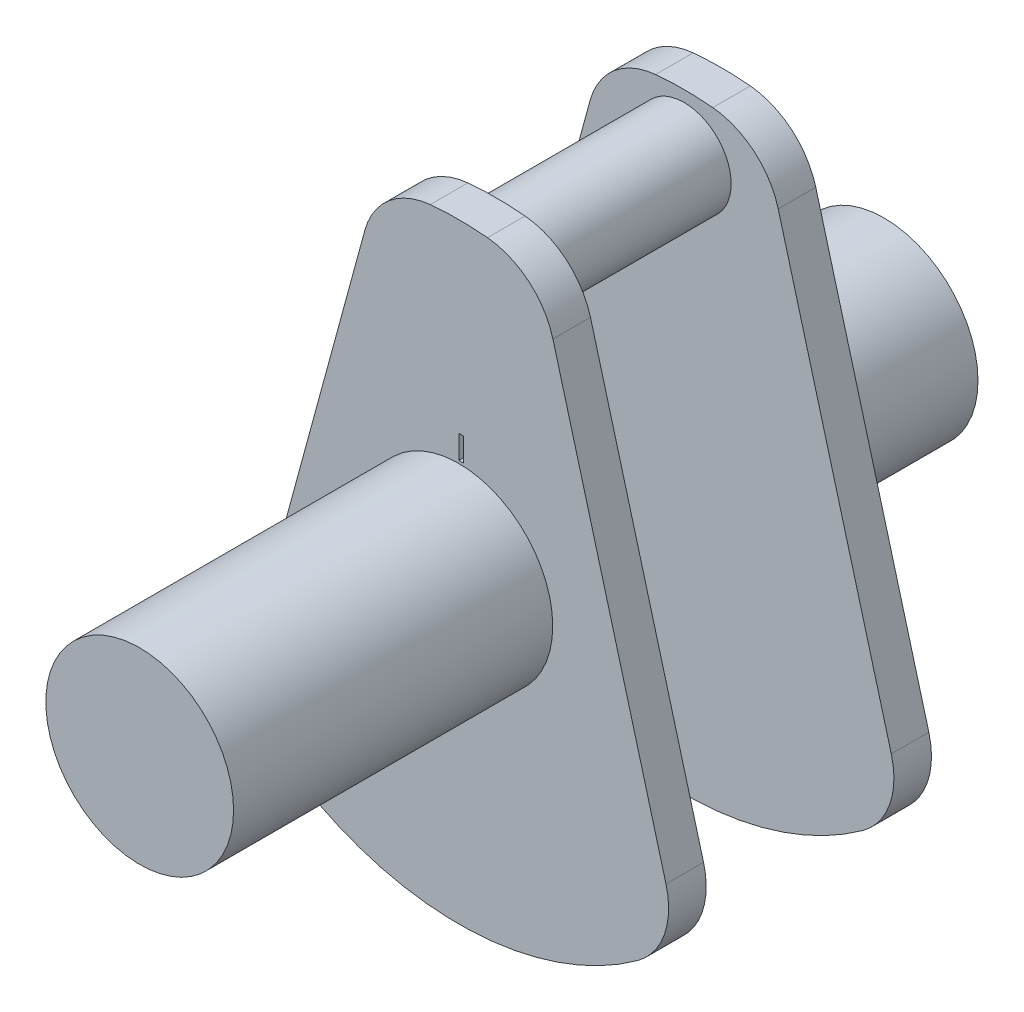
SolidWorks part; units mm, degrees
ref_plane "Front Plane" through (0, 0, 0) normal (0, 0, 1) x (1, 0, 0)
ref_plane "Top Plane" through (0, 0, 0) normal (0, 1, 0) x (1, 0, 0)
ref_plane "Right Plane" through (0, 0, 0) normal (1, 0, 0) x (0, 0, -1)
sketch "Sketch1" plane through (0, 0, 0) normal (0, 0, 1) x (1, 0, 0)
  line L0 (-2.0038, 5.2985) -> (-4.4127, -3.5522)
  line L1 (0, 6.5) -> (0, -6.5) construction
  line L2 (2.0038, 5.2985) -> (4.4127, -3.5522)
  arc A0 (-3.8056, -5.2695) -> (3.8056, -5.2695) centre (0, 0) ccw
  arc A1 (0.6102, 6.4713) -> (-0.6102, 6.4713) centre (0, 0) ccw
  arc A2 (2.0038, 5.2985) -> (0.6102, 6.4713) centre (0.46, 4.8784) ccw
  arc A3 (-2.0038, 5.2985) -> (-0.6102, 6.4713) centre (-0.46, 4.8784) cw
  arc A4 (-4.4127, -3.5522) -> (-3.8056, -5.2695) centre (-2.8688, -3.9724) ccw
  arc A5 (4.4127, -3.5522) -> (3.8056, -5.2695) centre (2.8688, -3.9724) cw
  point P10 (1.7415, 6.2624)
  point P13 (-1.7415, 6.2624)
  point P16 (-4.675, -4.516)
  point P19 (4.675, -4.516)
  dimension "D1" = 13
  dimension "D4" = 1.6
  dimension "D5" = 1.6
  dimension "D2" = 30.45
  dimension "D3" = 0.92
extrude "Boss-Extrude1" add sketch "Sketch1" along normal blind 0.8
sketch "Sketch3" plane through (0, 0, 0.8) normal (0, 0, 1) x (1, 0, 0)
  line L0 (0, 6.7111) -> (0, 5.26) construction
  circle A0 centre (0, 5.26) radius 1
  dimension "D1" = 2
  dimension "D2" = 5.26
extrude "Boss-Extrude2" add sketch "Sketch3" along normal blind 2
sketch "Sketch4" plane through (0, 0, 0) normal (0, 0, -1) x (-1, 0, 0)
  circle A0 centre (0, 0) radius 2
  dimension "D1" = 4
extrude "Boss-Extrude3" add sketch "Sketch4" along normal blind 3.46
mirror "Mirror1" about plane through (0, 5.26, 2.8) normal (0, 0, 1) of bodies 103
sketch "Sketch5" plane through (0, 0, 9.06) normal (0, 0, 1) x (1, 0, 0)
  circle A0 centre (0, 0) radius 2 construction
  circle A1 centre (0, 0) radius 2
extrude "Boss-Extrude4" add sketch "Sketch5" along normal blind 3.34
sketch "Sketch6" plane through (0, 0, 5.6) normal (0, 0, 1) x (1, 0, 0)
  line L0 (0, 0.5961) -> (0, 6.3899) construction
  line L2 (0, 2.5562) -> (0.1, 2.5562)
  line L3 (0, 2.5562) -> (0, 2.0562)
  line L4 (0, 2.0562) -> (0.1, 2.0562)
  line L5 (0.1, 2.5562) -> (0.1, 2.0562)
  dimension "D1" = 0.1
  dimension "D2" = 0.5
extrude "Cut-Extrude1" cut sketch "Sketch6" against normal blind 0.1
